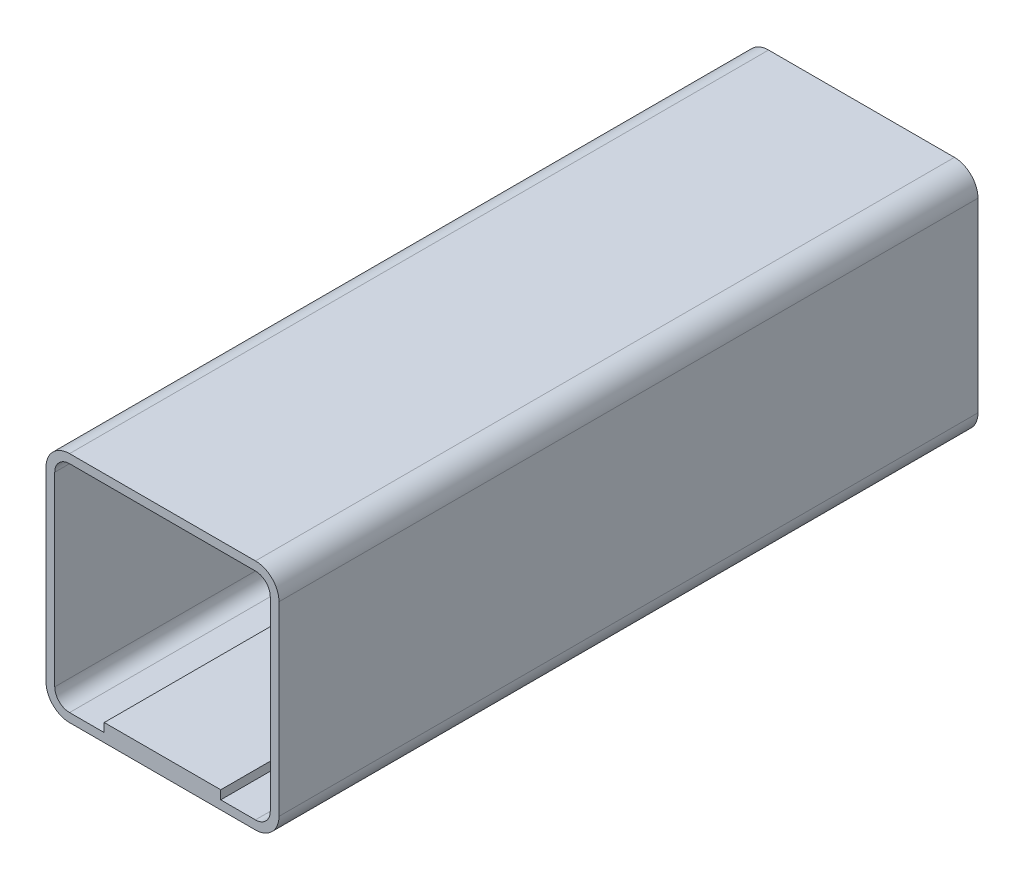
SolidWorks part; units mm, degrees
material "Polyurethane Foam Rigid"
ref_plane "Front Plane" through (0, 0, 0) normal (0, 0, 1) x (1, 0, 0)
ref_plane "Top Plane" through (0, 0, 0) normal (0, 1, 0) x (1, 0, 0)
ref_plane "Right Plane" through (0, 0, 0) normal (1, 0, 0) x (0, 0, -1)
sketch "Sketch1" plane through (0, 0, 0) normal (0, 0, 1) x (1, 0, 0)
  line L0 (-59.737, 59.737) -> (59.737, -59.737) construction
  line L1 (-50.6524, 63.5) -> (50.6524, 63.5)
  line L2 (-63.5, 50.6524) -> (-63.5, -50.6524)
  line L3 (-50.6524, -63.5) -> (50.6524, -63.5)
  line L4 (63.5, 50.6524) -> (63.5, -50.6524)
  arc A0 (63.5, 50.6524) -> (50.6524, 63.5) centre (50.6524, 50.6524) ccw
  arc A1 (50.6524, -63.5) -> (63.5, -50.6524) centre (50.6524, -50.6524) ccw
  arc A2 (-50.6524, -63.5) -> (-63.5, -50.6524) centre (-50.6524, -50.6524) cw
  arc A3 (-63.5, 50.6524) -> (-50.6524, 63.5) centre (-50.6524, 50.6524) cw
  point P0 (0, 0)
  point P1 (0, 0)
  point P18 (59.737, -59.737)
  dimension "D2" = 12.8476
  dimension "D3" = 12.8476
  dimension "D1" = 127
  dimension "D4" = 127
extrude "Boss-Extrude1" add sketch "Sketch1" against normal blind 381 contours L1 A0 L4 A1 L3 A2 L2 A3
shell "Shell1" thickness 4.7625
sketch "Sketch3" plane through (0, 0, 0) normal (0, 0, 1) x (1, 0, 0)
  line L0 (-31.75, -58.7375) -> (31.75, -58.7375)
  line L1 (-50.6524, -58.7375) -> (50.6524, -58.7375) construction
  line L2 (0, -58.7375) -> (0, 0) construction
  line L3 (-31.75, -58.7375) -> (-31.75, -53.975)
  line L4 (-31.75, -53.975) -> (31.75, -53.975)
  line L5 (31.75, -53.975) -> (31.75, -58.7375)
  point P5 (0, -58.7375)
  dimension "D1" = 63.5
  dimension "D2" = 4.7625
extrude "Boss-Extrude2" add sketch "Sketch3" against normal up to surface (381 mm away) up to face at (0, 0, -381)
equation "\"span\"= 48"
equation "\"wing_chord\"= 9"
equation "\"fuse_len\"= 15"
equation "\"fuse_height\"= 5"
equation "\"fuse_wid\"= 5"
equation "\"D1@Boss-Extrude1\"= \"fuse_len\""
equation "\"D1@Sketch1\"= \"fuse_height\""
equation "\"D4@Sketch1\"= \"fuse_wid\""
equation "\"D1@Sketch3\"=\"fuse_wid\"/2"
equation "\"D2@Sketch3\"=3/16"
equation "\"foam_t\"= 0.1875"
equation "\"fuse_inner_arc_length\" = 0.5"
equation "\"fuse_inner_r\" = \"fuse_inner_arc_length\" * 4 / (2*pi)"
equation "\"fuse_outer_r\" = \"fuse_inner_r\" + \"foam_t\""
equation "\"main_spar_len\"= 36"
equation "\"x_fuse_to_wing\"= 3"
equation "\"x_cg_from_le\"= 2.25"
equation "\"boom_len\"= 30"
equation "\"wing_angle\"= 1.5"
equation "\"boom_d\"= 0.75"
equation "\"wing_spar_d\"= 0.375"
equation "\"wing_spar_l\"= 48"
equation "\"wing_spar_spacing\"= 1.35"
equation "\"wing_mount_l\"= 2.5"
equation "\"wing_mount_bolt_spacing\" = \"wing_mount_l\" * 0.5"
equation "\"boom_mount_l\"= 1"
equation "\"vstab_span\"= 6.5"
equation "\"hstab_span\"= 15.25"
equation "\"tail_chord\"= 5"
equation "\"D2@Sketch1\"= \"fuse_outer_r\""
equation "\"D3@Sketch1\"= \"fuse_outer_r\""
equation "\"fuse_inner_h\" = \"fuse_height\" - 2 * \"foam_t\""
equation "\"fuse_inner_w\" = \"fuse_wid\" - 2 * \"fuse_outer_r\""
